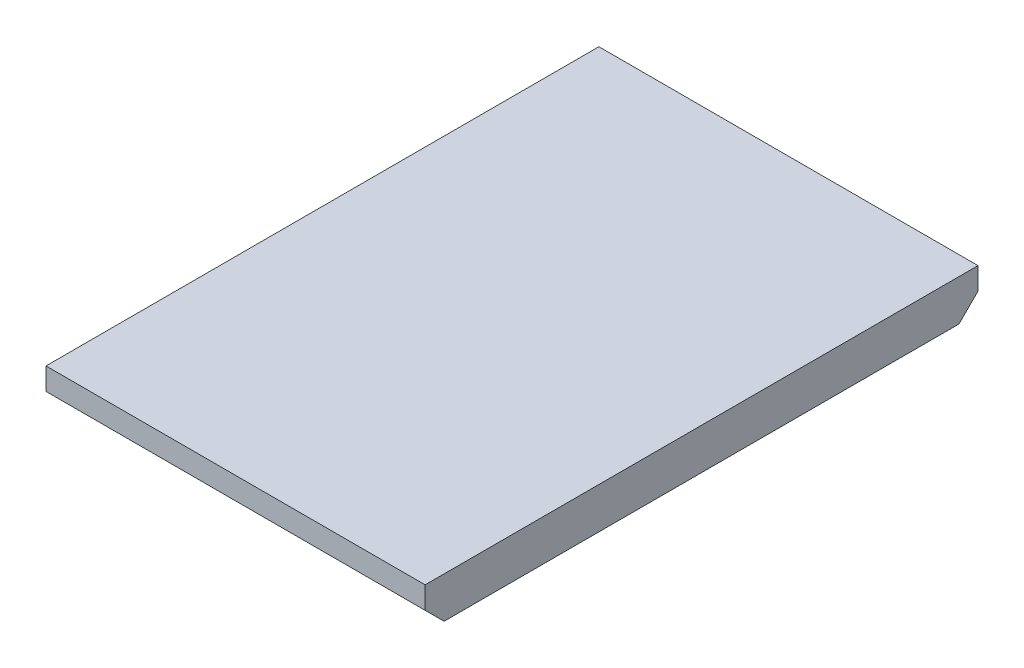
SolidWorks part; units mm, degrees
ref_plane "Front Plane" through (0, 0, 0) normal (0, 0, 1) x (1, 0, 0)
ref_plane "Top Plane" through (0, 0, 0) normal (0, 1, 0) x (1, 0, 0)
ref_plane "Right Plane" through (0, 0, 0) normal (1, 0, 0) x (0, 0, -1)
sketch "Sketch1" plane through (0, 0, 0) normal (1, 0, 0) x (0, 0, -1)
  line L0 (17.5, 0) -> (-17.5, 0)
  line L1 (-17.5, 0) -> (-17.5, -1.4)
  line L2 (-17.5, -1.4) -> (-16.3, -2.6)
  line L3 (-16.3, -2.6) -> (16.3, -2.6)
  line L4 (16.3, -2.6) -> (17.5, -1.4)
  line L5 (17.5, -1.4) -> (17.5, 0)
extrude "Boss-Extrude1" add sketch "Sketch1" along normal mid plane 24
